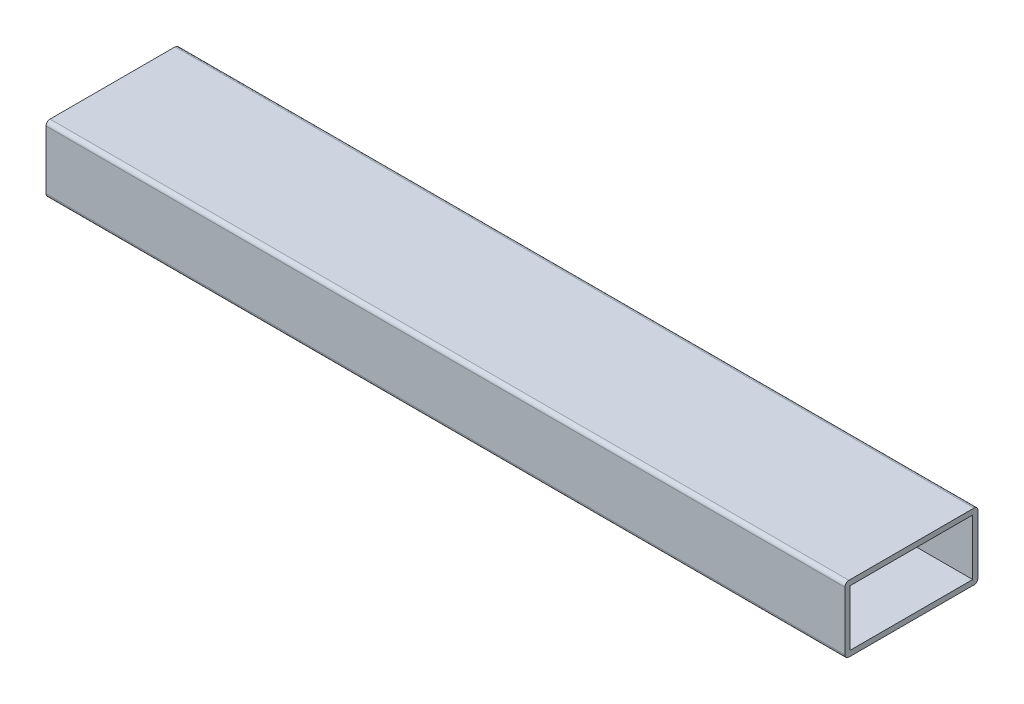
SolidWorks part; units mm, degrees
ref_plane "Front Plane" through (0, 0, 0) normal (0, 0, 1) x (1, 0, 0)
ref_plane "Top Plane" through (0, 0, 0) normal (0, 1, 0) x (1, 0, 0)
ref_plane "Right Plane" through (0, 0, 0) normal (1, 0, 0) x (0, 0, -1)
sketch "Sketch1" plane through (0, 0, 0) normal (1, 0, 0) x (0, 0, -1)
  line L1 (-23.5, 12.5) -> (23.5, 12.5)
  line L2 (-25, 11) -> (-25, -11)
  line L3 (-23.5, -12.5) -> (23.5, -12.5)
  line L4 (25, 11) -> (25, -11)
  line L5 (-25, 12.5) -> (25, -12.5) construction
  line L6 (-25, -12.5) -> (25, 12.5) construction
  arc A0 (-23.5, -12.5) -> (-25, -11) centre (-23.5, -11) cw
  arc A1 (23.5, -12.5) -> (25, -11) centre (23.5, -11) ccw
  arc A2 (25, 11) -> (23.5, 12.5) centre (23.5, 11) ccw
  arc A3 (-25, 11) -> (-23.5, 12.5) centre (-23.5, 11) cw
  point P0 (0, 0)
  dimension "D3" = 1.5
  dimension "D1" = 50
  dimension "D2" = 25
extrude "Boss-Extrude1" add sketch "Sketch1" along normal mid plane 300
shell "Shell1" thickness 2
